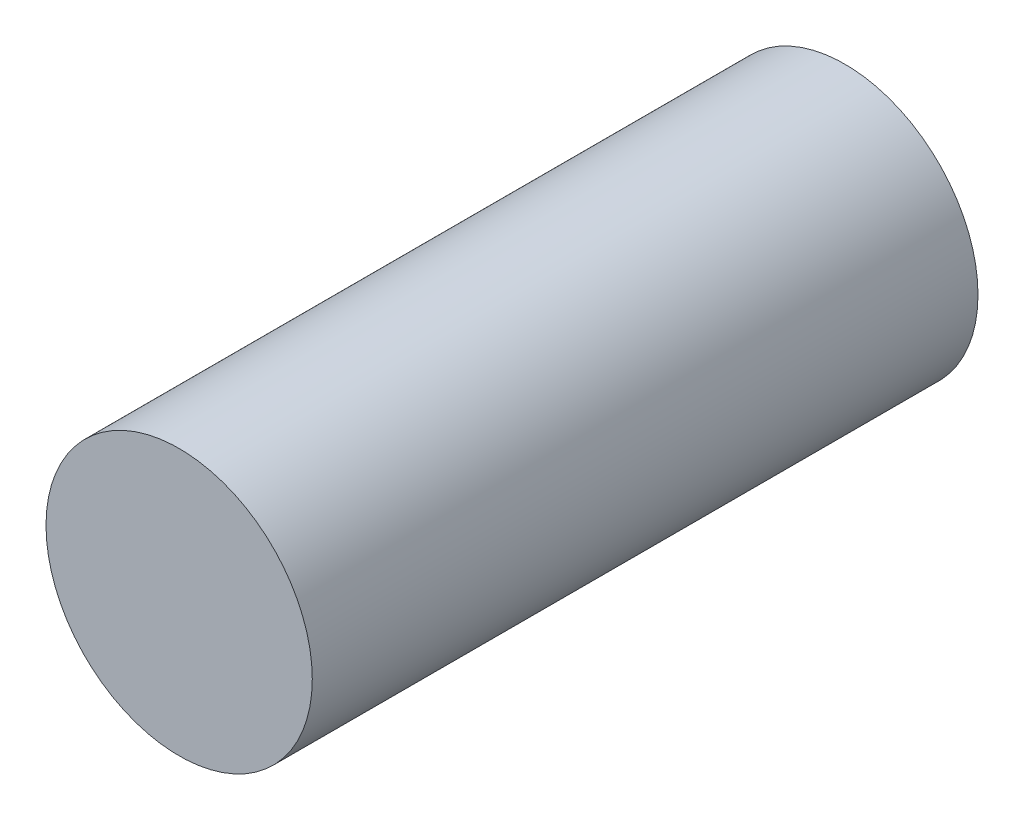
SolidWorks part; units mm, degrees
ref_plane "Plano frontal" through (0, 0, 0) normal (0, 0, 1) x (1, 0, 0)
ref_plane "Plano superior" through (0, 0, 0) normal (0, 1, 0) x (1, 0, 0)
ref_plane "Plano direito" through (0, 0, 0) normal (1, 0, 0) x (0, 0, -1)
sketch "Esboço1" plane through (0, 0, 0) normal (0, 0, 1) x (1, 0, 0)
  circle A0 centre (0, 0) radius 2
extrude "Ressalto-extrusão1" add sketch "Esboço1" along normal blind 10
